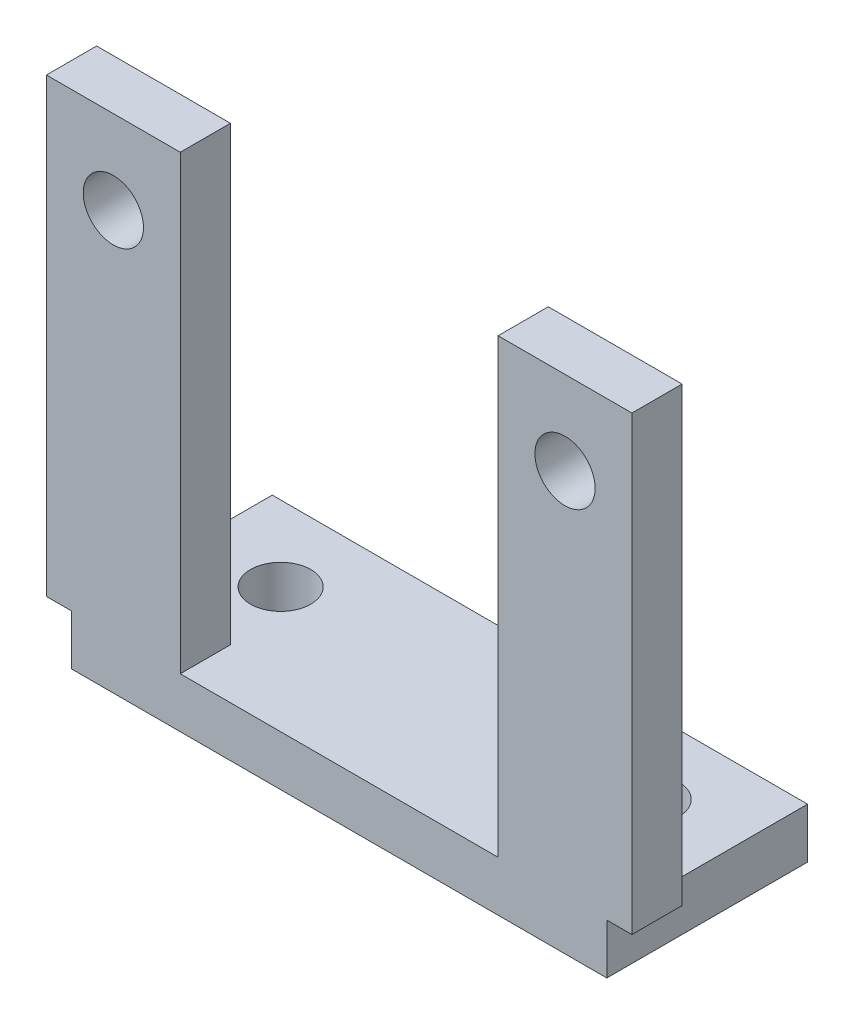
SolidWorks part; units mm, degrees
ref_plane "前视基准面" through (0, 0, 0) normal (0, 0, 1) x (1, 0, 0)
ref_plane "上视基准面" through (0, 0, 0) normal (0, 1, 0) x (1, 0, 0)
ref_plane "右视基准面" through (0, 0, 0) normal (1, 0, 0) x (0, 0, -1)
sketch "草图1" plane through (0, 0, 0) normal (0, 1, 0) x (1, 0, 0)
  line L0 (-16, 9) -> (16, 9)
  line L1 (16, 9) -> (16, -3)
  line L2 (16, -3) -> (-16, -3)
  line L3 (-16, -3) -> (-16, 9)
  dimension "D1" = 16
  dimension "D2" = 9
  dimension "D3" = 16
  dimension "D4" = 9
  dimension "D5" = 16
  dimension "D6" = 3
  dimension "D7" = 16
  dimension "D8" = 3
extrude "测距小底脚32x12_厚3_单向3mm" add sketch "草图1" along normal blind 3
sketch "草图2" plane through (0, 0, 0) normal (0, 0, 1) x (1, 0, 0)
  line L0 (-17.5, 3) -> (-9.5, 3)
  line L1 (-9.5, 3) -> (-9.5, 30)
  line L2 (-9.5, 30) -> (-17.5, 30)
  line L3 (-17.5, 30) -> (-17.5, 3)
  line L4 (9.5, 3) -> (17.5, 3)
  line L5 (17.5, 3) -> (17.5, 30)
  line L6 (17.5, 30) -> (9.5, 30)
  line L7 (9.5, 30) -> (9.5, 3)
  dimension "D1" = 17.5
  dimension "D2" = 3
  dimension "D3" = 9.5
  dimension "D4" = 3
  dimension "D5" = 9.5
  dimension "D6" = 30
  dimension "D7" = 17.5
  dimension "D8" = 30
  dimension "D9" = 9.5
  dimension "D10" = 3
  dimension "D11" = 17.5
  dimension "D12" = 3
  dimension "D13" = 17.5
  dimension "D14" = 30
  dimension "D15" = 9.5
  dimension "D16" = 30
extrude "两根支撑臂厚3_去掉大框和加强筋" add sketch "草图2" along normal blind 3
sketch "草图3" plane through (0, 0, 0) normal (0, 0, 1) x (1, 0, 0)
  circle A0 centre (-13.5, 25) radius 1.8
  circle A1 centre (13.5, 25) radius 1.8
  dimension "D1" = 3.6
  dimension "D2" = 13.5
  dimension "D3" = 13.5
  dimension "D4" = 25
extrude "背板原孔3.6_只接下排两孔距27_贯穿" cut sketch "草图3" along normal blind 3
sketch "草图4" plane through (0, 0, 0) normal (0, 1, 0) x (1, 0, 0)
  circle A0 centre (-11, 4.5) radius 1.8
  circle A1 centre (11, 4.5) radius 1.8
  dimension "D1" = 3.6
  dimension "D2" = 11
  dimension "D3" = 11
  dimension "D4" = 4.5
extrude "底脚圆孔_无长槽" cut sketch "草图4" along normal blind 3
